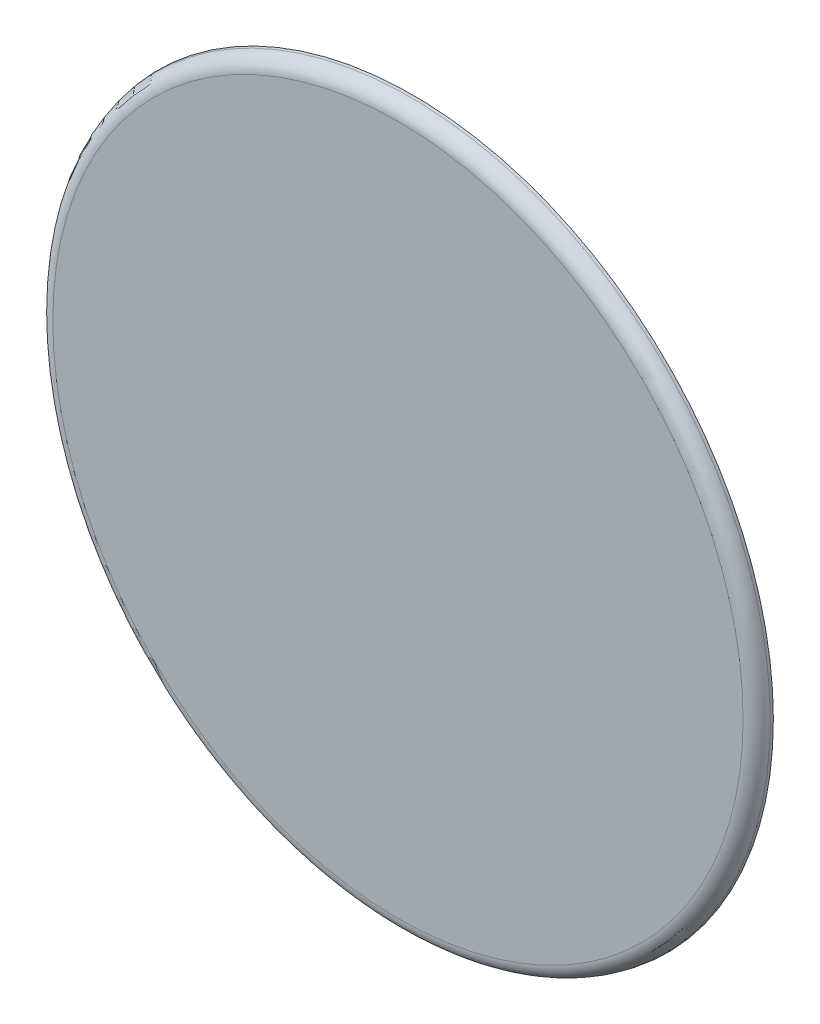
SolidWorks part; units mm, degrees
ref_plane "Front" through (0, 0, 0) normal (0, 0, 1) x (1, 0, 0)
ref_plane "Top" through (0, 0, 0) normal (0, 1, 0) x (1, 0, 0)
ref_plane "Right" through (0, 0, 0) normal (1, 0, 0) x (0, 0, -1)
sketch "Sketch1" plane through (0, 0, 0) normal (0, 0, 1) x (1, 0, 0)
  circle A0 centre (0, 0) radius 240
  dimension "D1" = 480
extrude "Boss-Extrude1" add sketch "Sketch1" along normal blind 10 draft 10
fillet "Fillet1" radius 10 1 edges at (238.2367, 0, 10)
